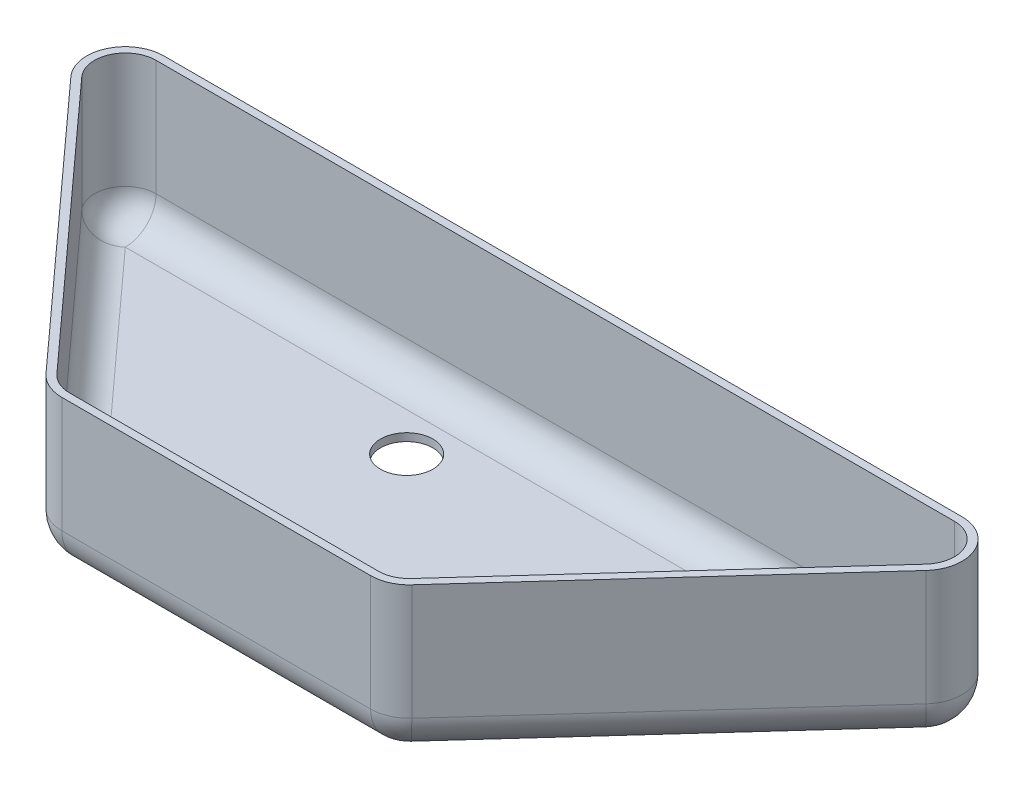
SolidWorks part; units mm, degrees
ref_plane "Front Plane" through (0, 0, 0) normal (0, 0, 1) x (1, 0, 0)
ref_plane "Top Plane" through (0, 0, 0) normal (0, 1, 0) x (1, 0, 0)
ref_plane "Right Plane" through (0, 0, 0) normal (1, 0, 0) x (0, 0, -1)
sketch "Sketch1" plane through (0, 0, 0) normal (0, 1, 0) x (1, 0, 0)
  line L5 (-50.8914, 0) -> (50.8914, 0)
  line L6 (-131.5929, 114.3) -> (131.5929, 114.3)
  line L8 (0, 0) -> (0, -114.3) construction
  line L9 (-140.9963, 93.0638) -> (-60.2948, 4.1638)
  line L10 (140.9963, 93.0638) -> (60.2948, 4.1638)
  line L11 (-87.0657, 37.4334) -> (-54.1539, 67.31) construction
  line L12 (-172.974, 109.3953) -> (172.974, 109.3953) construction
  line L13 (-172.974, 109.3953) -> (-69.215, -4.9047) construction
  line L14 (-92.8455, 45.4294) -> (-15.4623, 45.4294) construction
  line L15 (-131.5929, 111.76) -> (131.5929, 111.76) construction
  line L16 (139.1156, 94.7711) -> (58.4141, 5.8711) construction
  line L17 (-50.8914, 2.54) -> (50.8914, 2.54) construction
  line L18 (-139.1156, 94.7711) -> (-58.4141, 5.8711) construction
  line L19 (-68.961, 17.4894) -> (68.961, 17.4894) construction
  line L20 (-54.1539, 67.31) -> (-54.1539, 111.76) construction
  line L21 (-54.1539, 67.31) -> (-92.8455, 45.4294) construction
  line L22 (-54.1539, 67.31) -> (-15.4623, 45.4294) construction
  line L23 (-69.215, -4.9047) -> (69.215, -4.9047) construction
  line L24 (172.974, 109.3953) -> (69.215, -4.9047) construction
  line L25 (0, 109.3953) -> (0, -4.9047) construction
  line L30 (-144.2929, 96.6953) -> (144.2929, 96.6953) construction
  line L31 (144.2929, 96.6953) -> (63.5914, 7.7953) construction
  line L32 (-63.5914, 7.7953) -> (63.5914, 7.7953) construction
  line L33 (-144.2929, 96.6953) -> (-63.5914, 7.7953) construction
  circle A1 centre (-54.1539, 67.31) radius 44.45 construction
  arc A2 (-50.8914, 0) -> (-60.2948, 4.1638) centre (-50.8914, 12.7) cw
  arc A3 (50.8914, 0) -> (60.2948, 4.1638) centre (50.8914, 12.7) ccw
  arc A4 (131.5929, 114.3) -> (140.9963, 93.0638) centre (131.5929, 101.6) cw
  arc A5 (-131.5929, 114.3) -> (-140.9963, 93.0638) centre (-131.5929, 101.6) ccw
  circle A6 centre (54.1539, 67.31) radius 44.45 construction
  arc A7 (131.5929, 111.76) -> (139.1156, 94.7711) centre (131.5929, 101.6) cw construction
  arc A8 (50.8914, 2.54) -> (58.4141, 5.8711) centre (50.8914, 12.7) ccw construction
  arc A9 (-50.8914, 2.54) -> (-58.4141, 5.8711) centre (-50.8914, 12.7) cw construction
  arc A10 (-131.5929, 111.76) -> (-139.1156, 94.7711) centre (-131.5929, 101.6) ccw construction
  point P3 (0, 0)
  point P8 (0, 114.3)
  point P12 (-56.515, 0)
  point P15 (56.515, 0)
  point P18 (160.274, 114.3)
  point P21 (-160.274, 114.3)
  point P23 (-54.1539, 111.76)
  point P51 (0, -4.9047)
  point P56 (103.9422, 52.2453)
  dimension "D5" = 12.7
  dimension "D4" = 88.9
  dimension "D1" = 320.548
  dimension "D2" = 47.768
  dimension "D3" = 114.3
  dimension "D6" = 113.03
  dimension "D7" = 2.54
  dimension "D8" = 137.922
  dimension "D9" = 27.94
  dimension "D10" = 238.977
  dimension "D11" = 345.948
  dimension "D12" = 138.43
  dimension "D13" = 114.3
  dimension "D14" = 47.768
  dimension "D15" = 12.7
  dimension "D16" = 4.9047
extrude "Boss-Extrude1" add sketch "Sketch1" along normal blind 50.8 contours A4 L6 A5 L9 A2 L5 A3 L10
fillet "Fillet1" radius 12.7 8 edges at (-143.2054, 0, -106.742) (0, 0, -114.3) (143.2054, 0, -106.742) (100.6455, 0, -48.6138) (56.0334, 0, -1.0875) (0, 0, 0) (-56.0334, 0, -1.0875) (-100.6455, 0, -48.6138)
shell "Shell1" thickness 2.54
sketch "Sketch2" plane through (0, 0, 0) normal (0, -1, 0) x (1, 0, 0)
  line L0 (-131.5929, -101.6) -> (131.5929, -101.6) construction
  circle A0 centre (-26.1272, -88.9) radius 8.636
  dimension "D2" = 17.272
  dimension "D1" = 12.7
extrude "Cut-Extrude1" cut sketch "Sketch2" against normal up to surface (2.54 mm away) up to face at (0, 2.54, -57.15)
